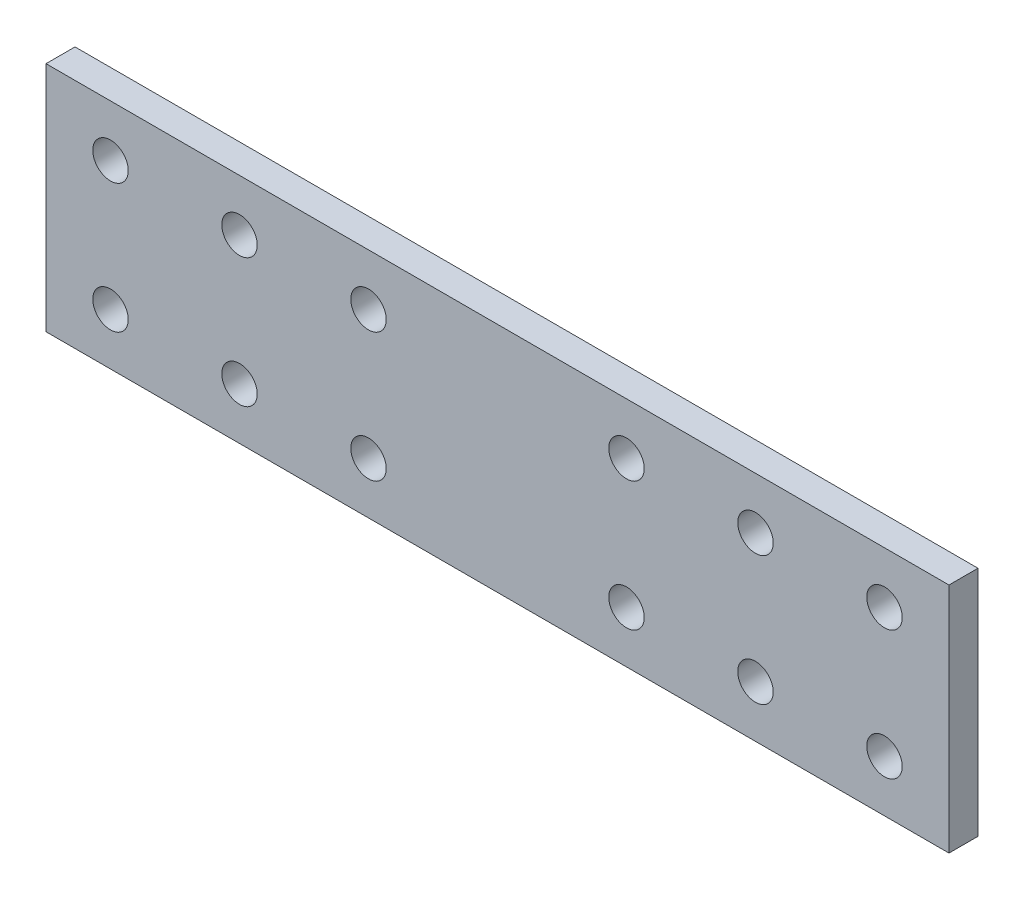
SolidWorks part; units mm, degrees
ref_plane "前视基准面" through (0, 0, 0) normal (0, 0, 1) x (1, 0, 0)
ref_plane "上视基准面" through (0, 0, 0) normal (0, 1, 0) x (1, 0, 0)
ref_plane "右视基准面" through (0, 0, 0) normal (1, 0, 0) x (0, 0, -1)
sketch "草图1" plane through (0, 0, 0) normal (0, 0, 1) x (1, 0, 0)
  line L1 (0, 0) -> (560, 0)
  line L2 (0, 0) -> (0, 144)
  line L3 (0, 144) -> (560, 144)
  line L4 (560, 0) -> (560, 144)
  dimension "D1" = 560
  dimension "D2" = 144
extrude "拉伸7" add sketch "草图1" along normal blind 18
sketch "草图2" plane through (0, 0, 18) normal (0, 0, 1) x (1, 0, 0)
  line L0 (0, 144) -> (0, 0) construction
  line L2 (0, 0) -> (560, 0) construction
  circle A0 centre (40, 112) radius 11
  dimension "D1" = 40
  dimension "D3" = 22
  dimension "D2" = 112
extrude "切除-拉伸2" cut sketch "草图2" against normal through all
pattern_linear "阵列(线性)2" count 2 spacing 80 along (0, -1, 0) count 3 spacing 80 along (1, 0, 0) of "切除-拉伸2"
pattern_linear "阵列(线性)4" count 2 spacing 320 along (1, 0, 0) of "切除-拉伸2", "阵列(线性)2"
